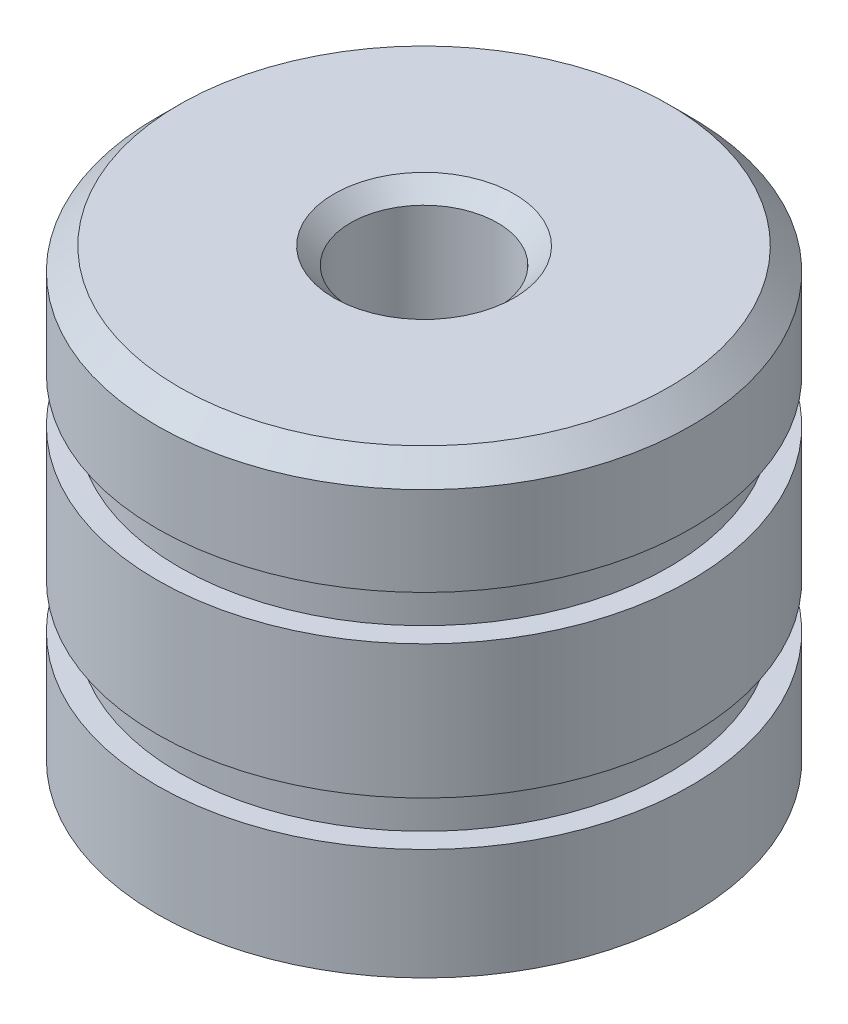
SolidWorks part; units mm, degrees
ref_plane "Front Plane" through (0, 0, 0) normal (0, 0, 1) x (1, 0, 0)
ref_plane "Top Plane" through (0, 0, 0) normal (0, 1, 0) x (1, 0, 0)
ref_plane "Right Plane" through (0, 0, 0) normal (1, 0, 0) x (0, 0, -1)
sketch "Sketch1" plane through (0, 0, 0) normal (0, 1, 0) x (1, 0, 0)
  circle A0 centre (0, 0) radius 6
  dimension "D1" = 12
extrude "Boss-Extrude1" add sketch "Sketch1" along normal mid plane 10
sketch "Sketch2" plane through (0, 5, 0) normal (0, 1, 0) x (1, 0, 0)
  circle A0 centre (0, 0) radius 6
  circle A1 centre (0, 0) radius 5.5
  dimension "D1" = 11
extrude "Cut-Extrude1" cut sketch "Sketch2" against normal blind 1 from offset 2.5 offset against normal yes
mirror "Mirror1" about plane through (0, 0, 0) normal (0, 1, 0) of "Cut-Extrude1"
chamfer "Chamfer1" distance 0.5 angle 45 1 edges at (0, 5, 6)
hole_wizard "M4x0.7 Tapped Hole1" positions "Sketch3" profile "Sketch4" tap size "M4x0.7" standard "ANSI Metric"
sketch "Sketch3" plane through (0, 5, 0) normal (0, 1, 0) x (1, 0, 0)
  point P0 (0, 0)
sketch "Sketch4" plane through (0, 5, 0) normal (1, 0, 0) x (0, 0, 1)
  line L0 (0, 0) -> (0, 8.9914)
  line L1 (0, 8.9914) -> (1.65, 8)
  line L2 (1.65, 8) -> (1.65, 0.375)
  line L3 (1.65, 0.375) -> (2.025, 0)
  line L5 (2.025, 0) -> (0, 0)
  line L6 (-1.65, 0.375) -> (-2.025, 0) construction
  line L10 (0, 8.9914) -> (-1.65, 8) construction
  line L11 (0, -6.35) -> (0, 107.95) construction
  dimension "Tap Drill Dia." = 3.3
  dimension "Tap Drill Depth" = 8
  dimension "Near C'Sink Dia." = 4.05
  dimension "Near C'Sink Angle" = 90
  dimension "Drill Angle" = 118
cosmetic thread "Hole Thread1" parameters "D1"=8, "D2"=4
